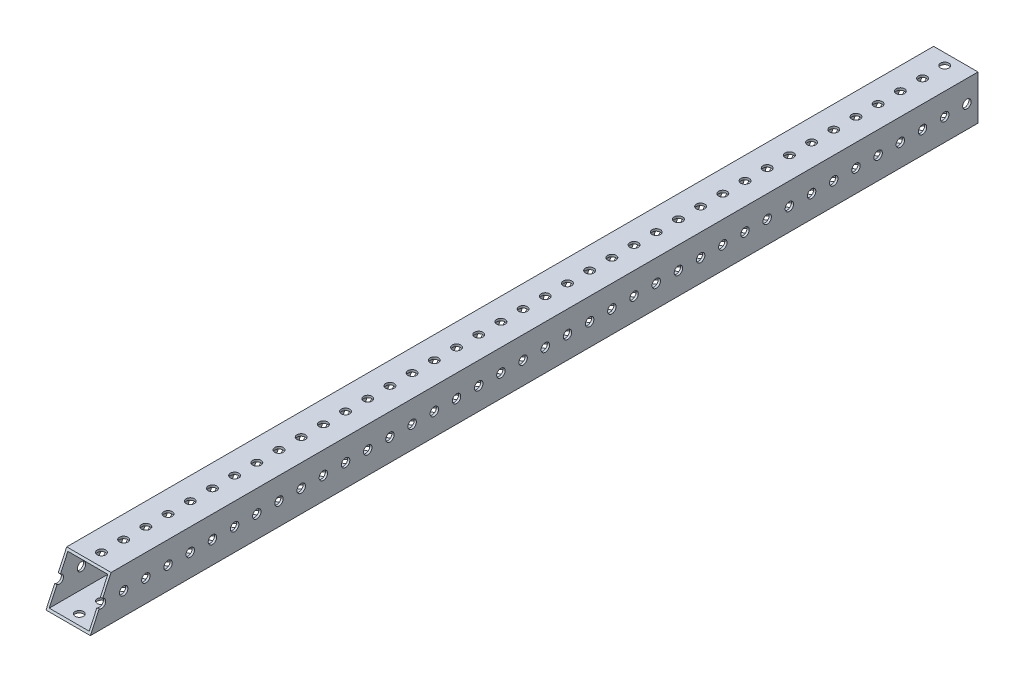
SolidWorks part; units mm, degrees
ref_plane "Front Plane" through (0, 0, 0) normal (0, 0, 1) x (1, 0, 0)
ref_plane "Top Plane" through (0, 0, 0) normal (0, 1, 0) x (1, 0, 0)
ref_plane "Right Plane" through (0, 0, 0) normal (1, 0, 0) x (0, 0, -1)
sketch "Sketch1" plane through (0, 0, 0) normal (0, 1, 0) x (1, 0, 0)
  line L1 (0, 0) -> (25.4, 0)
  line L2 (0, 0) -> (0, 508)
  line L3 (0, 508) -> (25.4, 508)
  line L4 (25.4, 0) -> (25.4, 508)
  dimension "D1" = 508
  dimension "D2" = 25.4
extrude "Boss-Extrude1" add sketch "Sketch1" along normal blind 25.4
sketch "Sketch2" plane through (0, 0, 0) normal (0, 0, 1) x (1, 0, 0)
  line L0 (0, 25.4) -> (25.4, 25.4) construction
  line L2 (25.4, 25.4) -> (25.4, 0) construction
  line L5 (1.27, 1.27) -> (24.13, 1.27)
  line L6 (1.27, 1.27) -> (1.27, 24.13)
  line L7 (1.27, 24.13) -> (24.13, 24.13)
  line L8 (24.13, 1.27) -> (24.13, 24.13)
  dimension "D1" = 22.86
  dimension "D2" = 1.27
  dimension "D3" = 1.27
extrude "Cut-Extrude1" cut sketch "Sketch2" against normal through all
sketch "Sketch3" plane through (0, 25.4, 0) normal (0, 1, 0) x (1, 0, 0)
  line L0 (25.4, 0) -> (25.4, 508) construction
  line L1 (0, 0) -> (25.4, 0) construction
  circle A0 centre (12.7, 6.35) radius 2.413
  circle A1 centre (12.7, 19.05) radius 2.413
  circle A2 centre (12.7, 31.75) radius 2.413
  circle A3 centre (12.7, 44.45) radius 2.413
  circle A4 centre (12.7, 57.15) radius 2.413
  circle A5 centre (12.7, 69.85) radius 2.413
  circle A6 centre (12.7, 82.55) radius 2.413
  circle A7 centre (12.7, 95.25) radius 2.413
  circle A8 centre (12.7, 107.95) radius 2.413
  circle A9 centre (12.7, 120.65) radius 2.413
  circle A10 centre (12.7, 133.35) radius 2.413
  circle A11 centre (12.7, 146.05) radius 2.413
  circle A12 centre (12.7, 158.75) radius 2.413
  circle A13 centre (12.7, 171.45) radius 2.413
  circle A14 centre (12.7, 184.15) radius 2.413
  circle A15 centre (12.7, 196.85) radius 2.413
  circle A16 centre (12.7, 209.55) radius 2.413
  circle A17 centre (12.7, 222.25) radius 2.413
  circle A18 centre (12.7, 234.95) radius 2.413
  circle A19 centre (12.7, 247.65) radius 2.413
  circle A20 centre (12.7, 260.35) radius 2.413
  circle A21 centre (12.7, 273.05) radius 2.413
  circle A22 centre (12.7, 285.75) radius 2.413
  circle A23 centre (12.7, 298.45) radius 2.413
  circle A24 centre (12.7, 311.15) radius 2.413
  circle A25 centre (12.7, 323.85) radius 2.413
  circle A26 centre (12.7, 336.55) radius 2.413
  circle A27 centre (12.7, 349.25) radius 2.413
  circle A28 centre (12.7, 361.95) radius 2.413
  circle A29 centre (12.7, 374.65) radius 2.413
  circle A30 centre (12.7, 387.35) radius 2.413
  circle A31 centre (12.7, 400.05) radius 2.413
  circle A32 centre (12.7, 412.75) radius 2.413
  circle A33 centre (12.7, 425.45) radius 2.413
  circle A34 centre (12.7, 438.15) radius 2.413
  circle A35 centre (12.7, 450.85) radius 2.413
  circle A36 centre (12.7, 463.55) radius 2.413
  circle A37 centre (12.7, 476.25) radius 2.413
  circle A38 centre (12.7, 488.95) radius 2.413
  circle A39 centre (12.7, 501.65) radius 2.413
  circle A40 centre (12.7, 514.35) radius 2.413
  circle A41 centre (12.7, 527.05) radius 2.413
  circle A42 centre (12.7, 539.75) radius 2.413
  circle A43 centre (12.7, 552.45) radius 2.413
  dimension "D1" = 12.7
  dimension "D2" = 6.35
  dimension "D3" = 4.826
  dimension "D4" = 44
extrude "Cut-Extrude2" cut sketch "Sketch3" against normal through all
sketch "Sketch4" plane through (0, 0, 0) normal (-1, 0, 0) x (0, 0, 1)
  line L0 (-508, 25.4) -> (0, 25.4) construction
  line L1 (0, 25.4) -> (0, 0) construction
  circle A0 centre (-6.35, 12.7) radius 2.413
  circle A1 centre (-19.05, 12.7) radius 2.413
  circle A2 centre (-31.75, 12.7) radius 2.413
  circle A3 centre (-44.45, 12.7) radius 2.413
  circle A4 centre (-57.15, 12.7) radius 2.413
  circle A5 centre (-69.85, 12.7) radius 2.413
  circle A6 centre (-82.55, 12.7) radius 2.413
  circle A7 centre (-95.25, 12.7) radius 2.413
  circle A8 centre (-107.95, 12.7) radius 2.413
  circle A9 centre (-120.65, 12.7) radius 2.413
  circle A10 centre (-133.35, 12.7) radius 2.413
  circle A11 centre (-146.05, 12.7) radius 2.413
  circle A12 centre (-158.75, 12.7) radius 2.413
  circle A13 centre (-171.45, 12.7) radius 2.413
  circle A14 centre (-184.15, 12.7) radius 2.413
  circle A15 centre (-196.85, 12.7) radius 2.413
  circle A16 centre (-209.55, 12.7) radius 2.413
  circle A17 centre (-222.25, 12.7) radius 2.413
  circle A18 centre (-234.95, 12.7) radius 2.413
  circle A19 centre (-247.65, 12.7) radius 2.413
  circle A20 centre (-260.35, 12.7) radius 2.413
  circle A21 centre (-273.05, 12.7) radius 2.413
  circle A22 centre (-285.75, 12.7) radius 2.413
  circle A23 centre (-298.45, 12.7) radius 2.413
  circle A24 centre (-311.15, 12.7) radius 2.413
  circle A25 centre (-323.85, 12.7) radius 2.413
  circle A26 centre (-336.55, 12.7) radius 2.413
  circle A27 centre (-349.25, 12.7) radius 2.413
  circle A28 centre (-361.95, 12.7) radius 2.413
  circle A29 centre (-374.65, 12.7) radius 2.413
  circle A30 centre (-387.35, 12.7) radius 2.413
  circle A31 centre (-400.05, 12.7) radius 2.413
  circle A32 centre (-412.75, 12.7) radius 2.413
  circle A33 centre (-425.45, 12.7) radius 2.413
  circle A34 centre (-438.15, 12.7) radius 2.413
  circle A35 centre (-450.85, 12.7) radius 2.413
  circle A36 centre (-463.55, 12.7) radius 2.413
  circle A37 centre (-476.25, 12.7) radius 2.413
  circle A38 centre (-488.95, 12.7) radius 2.413
  circle A39 centre (-501.65, 12.7) radius 2.413
  circle A40 centre (-514.35, 12.7) radius 2.413
  circle A41 centre (-527.05, 12.7) radius 2.413
  circle A42 centre (-539.75, 12.7) radius 2.413
  circle A43 centre (-552.45, 12.7) radius 2.413
  dimension "D1" = 12.7
  dimension "D2" = 6.35
  dimension "D3" = 4.826
  dimension "D4" = 44
extrude "Cut-Extrude3" cut sketch "Sketch4" against normal through all
sketch "Sketch6" plane through (25.4, 0, 0) normal (1, 0, 0) x (0, 0, -1)
  line L0 (0, 0) -> (11.8442, 25.4)
  line L1 (0, 25.4) -> (508, 25.4) construction
  line L2 (11.8442, 25.4) -> (0, 25.4)
  line L3 (0, 25.4) -> (0, 0)
  dimension "D1" = 25
extrude "Cut-Extrude4" cut sketch "Sketch6" against normal through all
